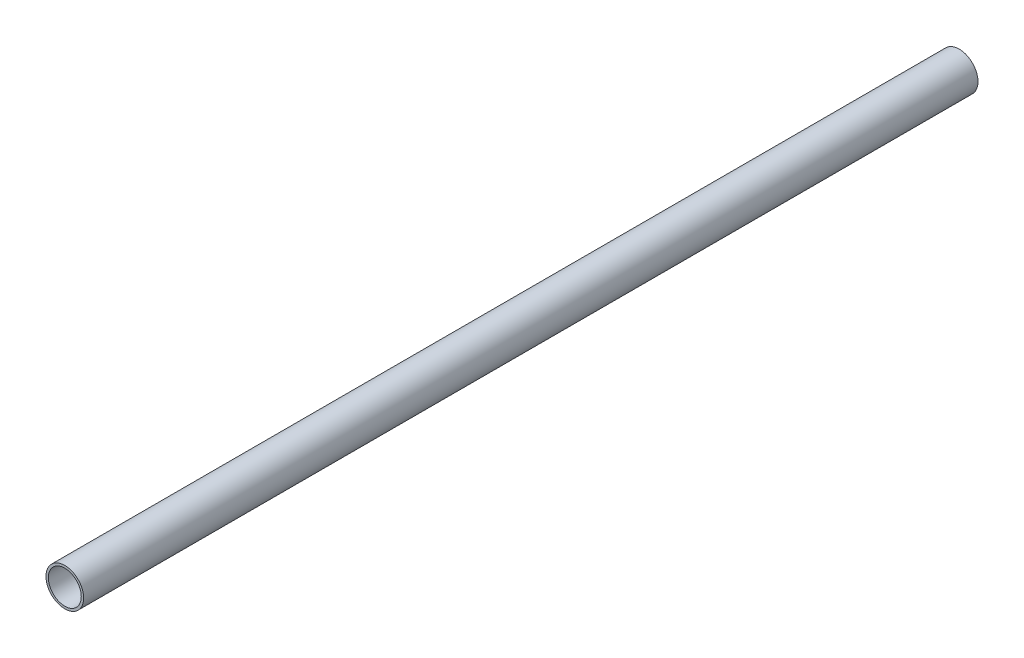
SolidWorks part; units mm, degrees
ref_plane "Ön Düzlem" through (0, 0, 0) normal (0, 0, 1) x (1, 0, 0)
ref_plane "Üst Düzlem" through (0, 0, 0) normal (0, 1, 0) x (1, 0, 0)
ref_plane "Sağ Düzlem" through (0, 0, 0) normal (1, 0, 0) x (0, 0, -1)
sketch "Çizim1" plane through (0, 0, 0) normal (0, 0, 1) x (1, 0, 0)
  circle A0 centre (0, 0) radius 7
  circle A1 centre (0, 0) radius 8
  dimension "D1" = 16
  dimension "D2" = 14
extrude "Yükseklik-Ekstrüzyon1" add sketch "Çizim1" along normal blind 380
